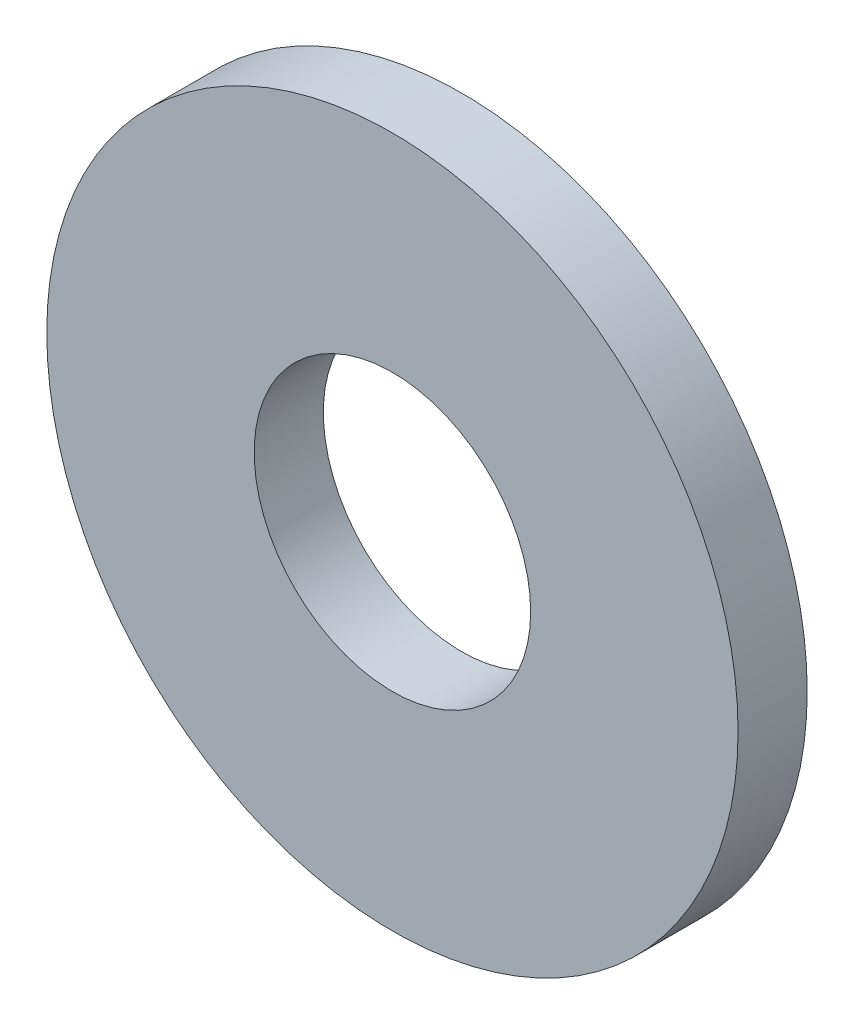
SolidWorks part; units mm, degrees
ref_plane "Plan de face" through (0, 0, 0) normal (0, 0, 1) x (1, 0, 0)
ref_plane "Plan de dessus" through (0, 0, 0) normal (0, 1, 0) x (1, 0, 0)
ref_plane "Plan de droite" through (0, 0, 0) normal (1, 0, 0) x (0, 0, -1)
sketch "Esquisse1" plane through (0, 0, 0) normal (0, 0, 1) x (1, 0, 0)
  circle A0 centre (0, 0) radius 5
  circle A1 centre (0, 0) radius 2
  dimension "D1" = 10
  dimension "D2" = 4
extrude "Boss.-Extru.1" add sketch "Esquisse1" along normal blind 1
